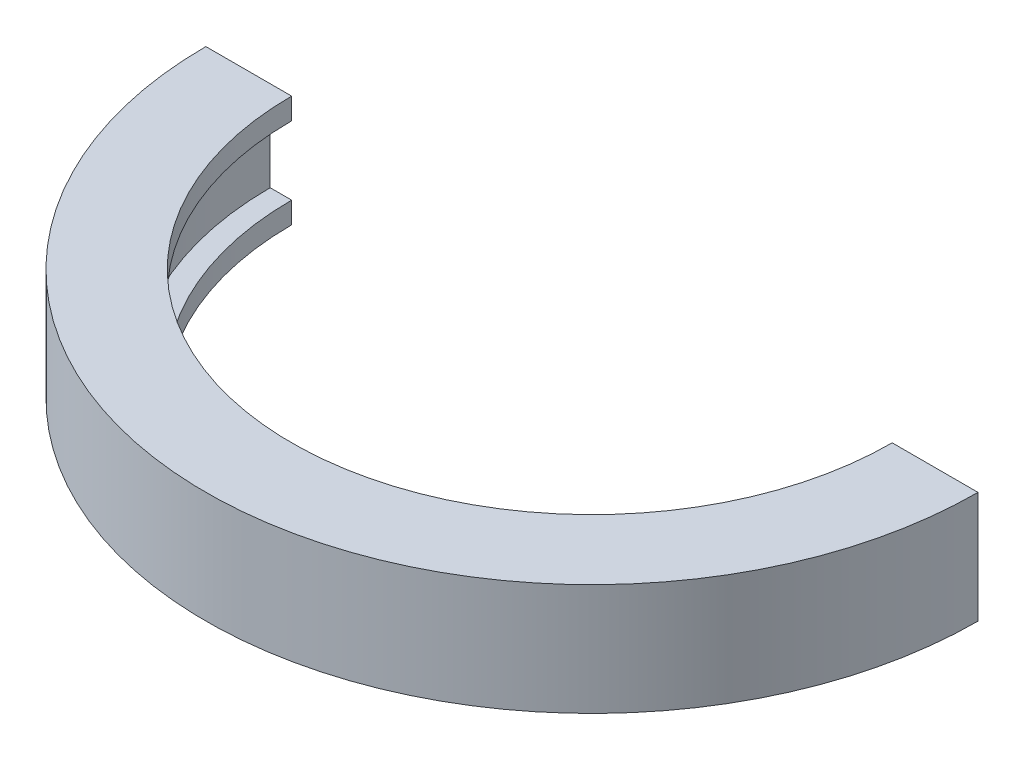
SolidWorks part; units mm, degrees
material "Nylon 6/10"
ref_plane "Front Plane" through (0, 0, 0) normal (0, 0, 1) x (1, 0, 0)
ref_plane "Top Plane" through (0, 0, 0) normal (0, 1, 0) x (1, 0, 0)
ref_plane "Right Plane" through (0, 0, 0) normal (1, 0, 0) x (0, 0, -1)
sketch "Sketch1" plane through (0, 0, 0) normal (0, 1, 0) x (1, 0, 0)
  line L4 (-79.1914, -3.156) -> (100.8086, -3.156)
  arc A0 (-59.1914, -3.156) -> (80.8086, -3.156) centre (10.8086, -3.156) ccw
  arc A1 (-79.1914, -3.156) -> (100.8086, -3.156) centre (10.8086, -3.156) ccw
  dimension "D1" = 70
  dimension "D2" = 180
extrude "Boss-Extrude1" add sketch "Sketch1" along normal mid plane 26
ref_axis "Axis1" through (10.8086, 13, 3.156) along (0, -1, 0)
sketch "Sketch2" plane through (0, 0, 3.156) normal (0, 0, -1) x (-1, 0, 0)
  line L1 (59.1914, -8) -> (64.1914, -8)
  line L2 (59.1914, -8) -> (59.1914, 8)
  line L3 (59.1914, 8) -> (64.1914, 8)
  line L4 (64.1914, -8) -> (64.1914, 8)
  line L5 (59.1914, 13) -> (59.1914, -13) construction
  line L6 (79.1914, -13) -> (59.1914, -13) construction
  line L7 (79.1914, 13) -> (59.1914, 13) construction
  line L8 (79.1914, 13) -> (79.1914, -13) construction
  dimension "D1" = 15
  dimension "D2" = 5
  dimension "D3" = 5
revolve "Cut-Revolve1" cut sketch "Sketch2" angle 360 about axis through (10.8086, 13, 3.156) along (0, -1, 0)
